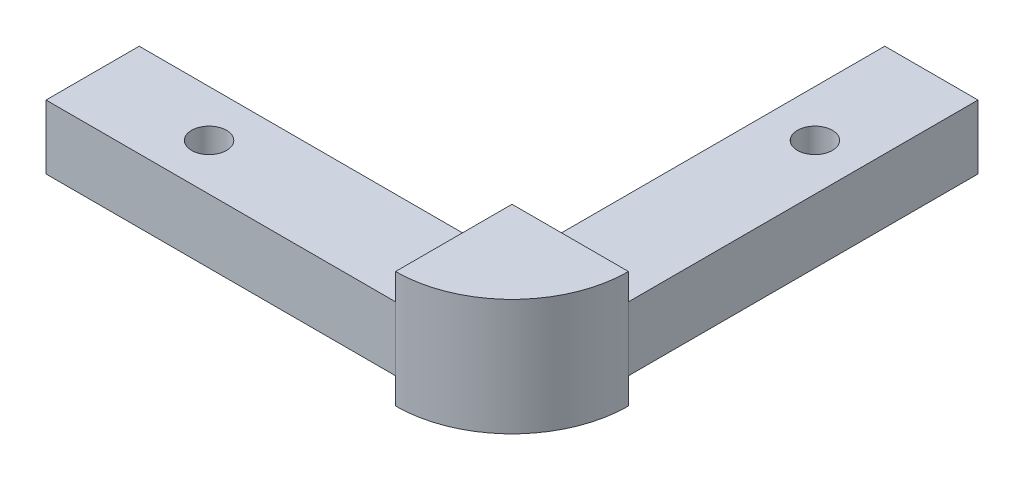
SolidWorks part; units mm, degrees
ref_plane "前视基准面" through (0, 0, 0) normal (0, 0, 1) x (1, 0, 0)
ref_plane "上视基准面" through (0, 0, 0) normal (0, 1, 0) x (1, 0, 0)
ref_plane "右视基准面" through (0, 0, 0) normal (1, 0, 0) x (0, 0, -1)
sketch "草图5" plane through (0, 0, 0) normal (0, 1, 0) x (1, 0, 0)
  line L1 (-34.3342, 14.7736) -> (-32.3342, 14.7736)
  line L2 (-34.3342, 14.7736) -> (-34.3342, 12.7736)
  line L6 (-24.3342, 14.7736) -> (-24.3342, 44.7736)
  line L7 (-24.3342, 44.7736) -> (-32.3342, 44.7736)
  line L8 (-32.3342, 14.7736) -> (-32.3342, 44.7736)
  line L9 (-34.3342, 4.7736) -> (-64.3342, 4.7736)
  line L11 (-34.3342, 12.7736) -> (-64.3342, 12.7736)
  line L12 (-64.3342, 4.7736) -> (-64.3342, 12.7736)
  arc A0 (-34.3342, 4.7736) -> (-24.3342, 14.7736) centre (-34.3342, 14.7736) ccw
  dimension "D1" = 30
  dimension "D3" = 10
  dimension "D2" = 30
  dimension "D4" = 8
  dimension "D5" = 8
  dimension "D6" = 2
  dimension "D7" = 2
extrude "凸台-拉伸5" add sketch "草图5" along normal blind 5.5
sketch "草图6" plane through (0, 5.5, 0) normal (0, 1, 0) x (1, 0, 0)
  line L5 (-34.3342, 14.7736) -> (-24.3342, 14.7736)
  line L6 (-34.3342, 14.7736) -> (-34.3342, 4.7736)
  arc A1 (-34.3342, 4.7736) -> (-24.3342, 14.7736) centre (-34.3342, 14.7736) ccw
extrude "凸台-拉伸7" add sketch "草图6" along normal blind 2.25 and the other way blind 7.75
sketch "草图7" plane through (0, 5.5, 0) normal (0, 1, 0) x (1, 0, 0)
  line L0 (-34.3342, 12.7736) -> (-34.3342, 4.7736) construction
  line L1 (-64.3342, 4.7736) -> (-34.3342, 4.7736) construction
  line L2 (-24.3342, 14.7736) -> (-24.3342, 44.7736) construction
  line L3 (-24.3342, 14.7736) -> (-32.3342, 14.7736) construction
  circle A0 centre (-54.3342, 8.7736) radius 1.5
  circle A1 centre (-28.3342, 34.7736) radius 1.5
  dimension "D1" = 20
  dimension "D3" = 4
  dimension "D2" = 4
  dimension "D4" = 20
extrude "切除-拉伸1" cut sketch "草图7" against normal blind 10
